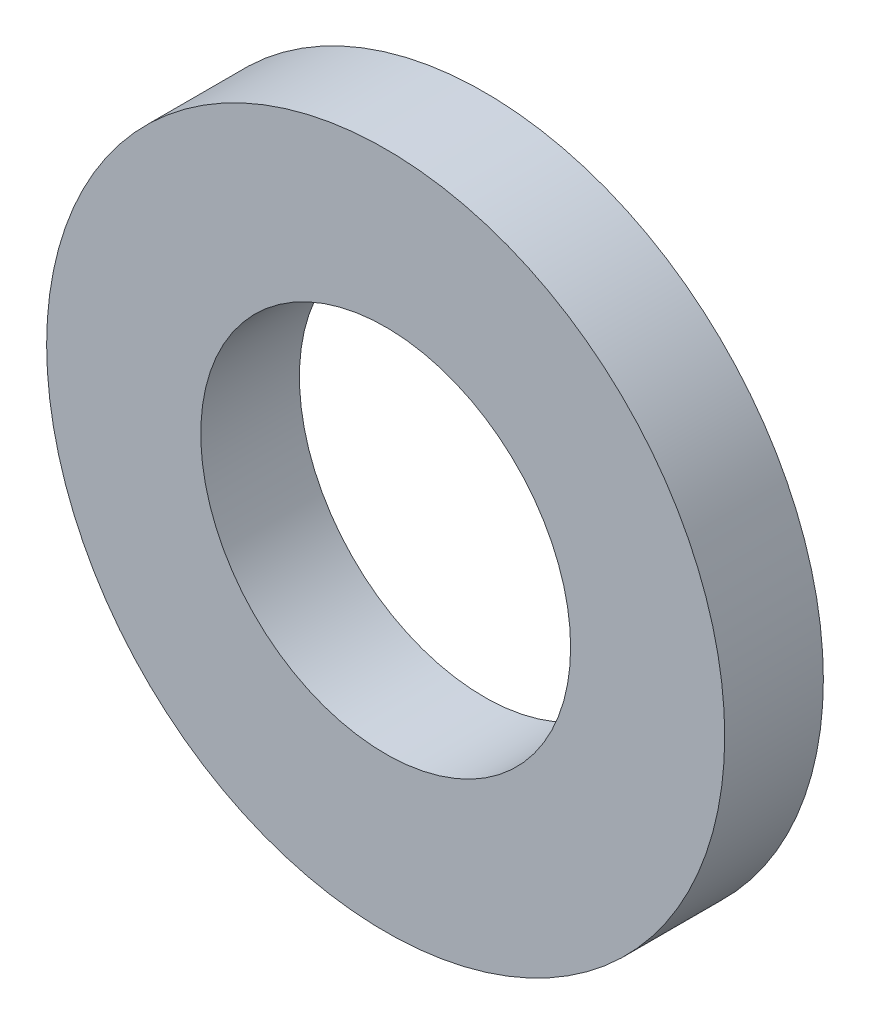
SolidWorks part; units mm, degrees
material "AISI 304"
ref_plane "前视基准面" through (0, 0, 0) normal (0, 0, 1) x (1, 0, 0)
ref_plane "上视基准面" through (0, 0, 0) normal (0, 1, 0) x (1, 0, 0)
ref_plane "右视基准面" through (0, 0, 0) normal (1, 0, 0) x (0, 0, -1)
sketch "草图1" plane through (0, 0, 0) normal (0, 0, 1) x (1, 0, 0)
  circle A0 centre (0, 0) radius 3
  circle A1 centre (0, 0) radius 5.5
  dimension "D1" = 6
  dimension "D2" = 11
extrude "凸台-拉伸1" add sketch "草图1" along normal blind 1.6
